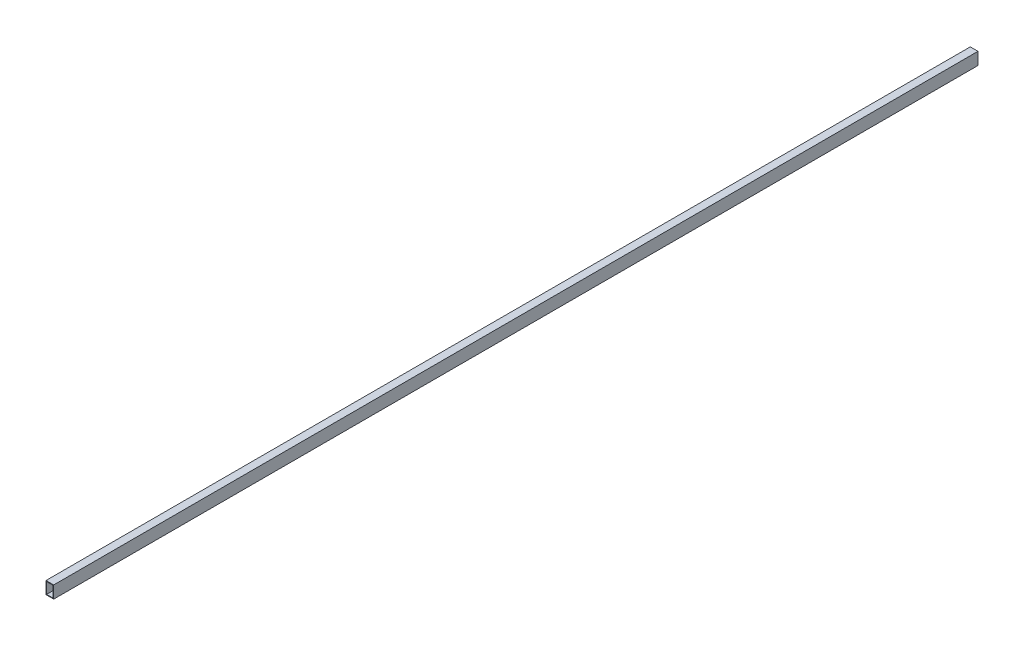
SolidWorks part; units mm, degrees
material "1060 Alloy"
ref_plane "Front Plane" through (0, 0, 0) normal (0, 0, 1) x (1, 0, 0)
ref_plane "Top Plane" through (0, 0, 0) normal (0, 1, 0) x (1, 0, 0)
ref_plane "Right Plane" through (0, 0, 0) normal (1, 0, 0) x (0, 0, -1)
sketch "Sketch1" plane through (0, 0, 0) normal (0, 0, 1) x (1, 0, 0)
  line L1 (-25, 40) -> (25, 40)
  line L2 (-25, 40) -> (-25, -40)
  line L3 (-25, -40) -> (25, -40)
  line L4 (25, 40) -> (25, -40)
  point P0 (0, 0)
  point P7 (0, 0)
  dimension "D1" = 80
  dimension "D2" = 50
extrude "Boss-Extrude1" add sketch "Sketch1" along normal blind 6000 contours L1 L4 L3 L2
sketch "Sketch2" plane through (0, 0, 0) normal (0, 0, -1) x (-1, 0, 0)
  line L1 (-21, 36) -> (21, 36)
  line L2 (-21, 36) -> (-21, -36)
  line L3 (-21, -36) -> (21, -36)
  line L4 (21, 36) -> (21, -36)
  line L5 (-21, 36) -> (21, -36) construction
  line L6 (-21, -36) -> (21, 36) construction
  point P0 (0, 0)
  dimension "D1" = 42
  dimension "D2" = 72
extrude "Cut-Extrude1" cut sketch "Sketch2" against normal blind 6000
